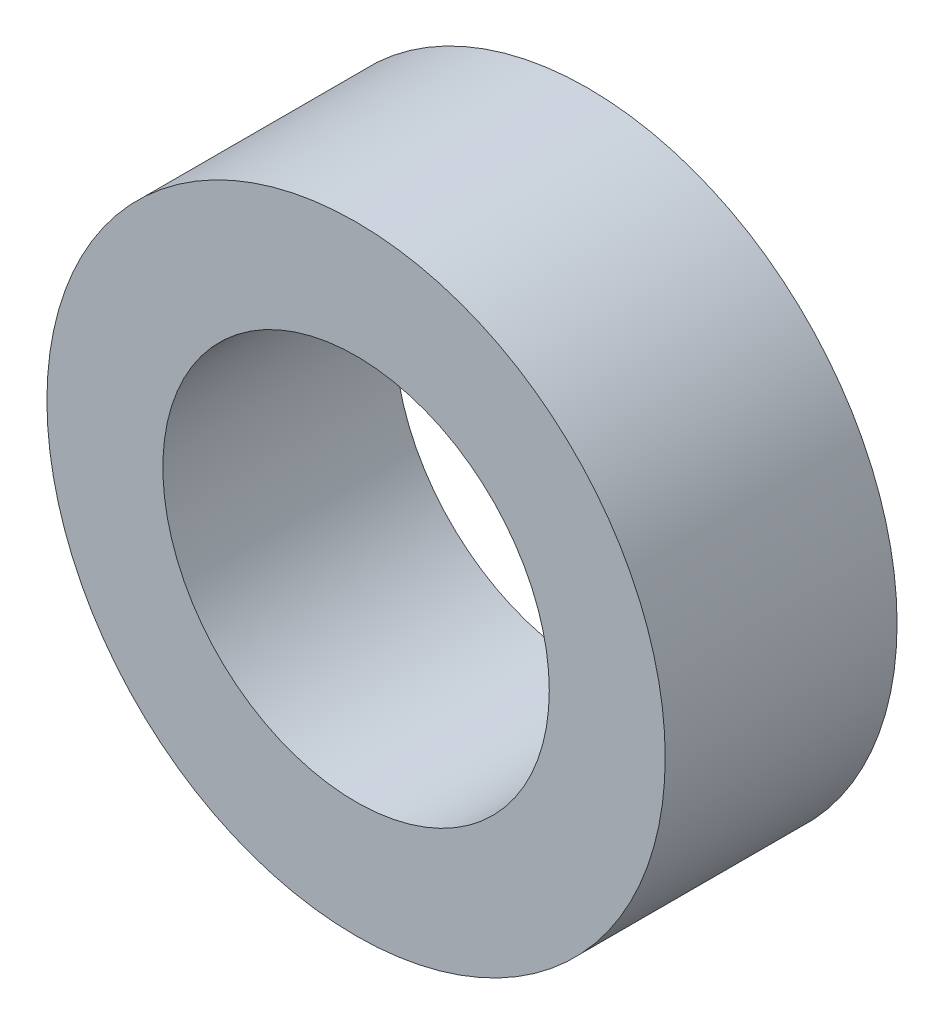
SolidWorks part; units mm, degrees
material "硅橡胶"
ref_plane "前视基准面" through (0, 0, 0) normal (0, 0, 1) x (1, 0, 0)
ref_plane "上视基准面" through (0, 0, 0) normal (0, 1, 0) x (1, 0, 0)
ref_plane "右视基准面" through (0, 0, 0) normal (1, 0, 0) x (0, 0, -1)
sketch "Sketch1" plane through (0, 0, 0) normal (0, 0, 1) x (1, 0, 0)
  circle A0 centre (0, 0) radius 8
  circle A1 centre (0, 0) radius 5
  dimension "D1" = 10
  dimension "D2" = 16
extrude "Extrude1" add sketch "Sketch1" along normal blind 6
